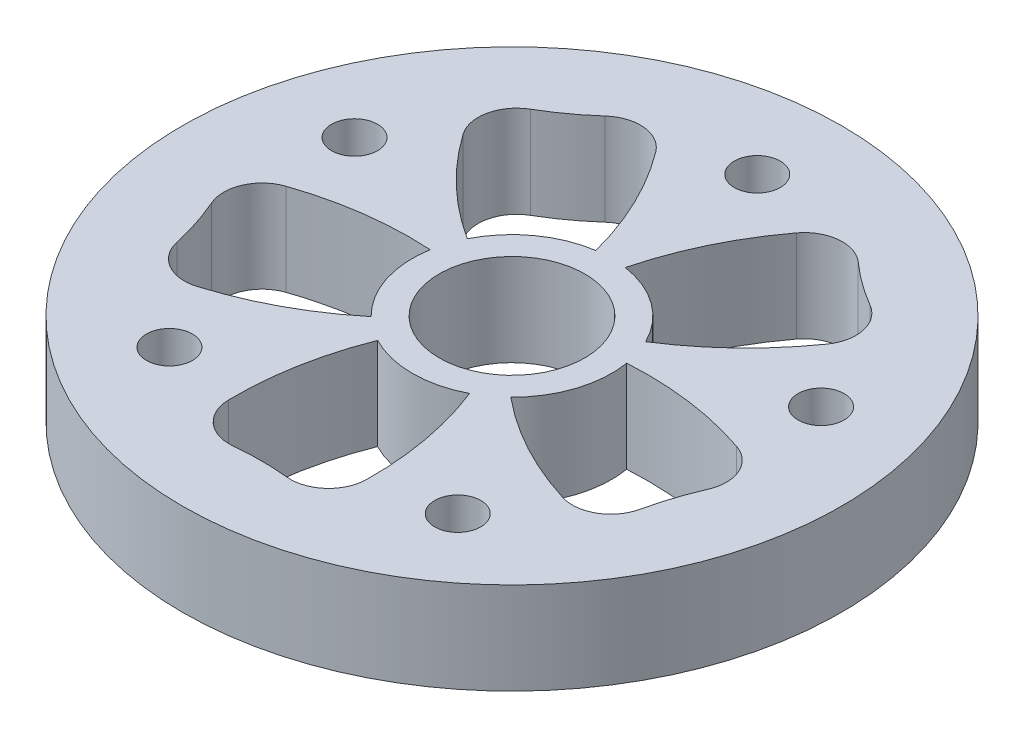
SolidWorks part; units mm, degrees
ref_plane "前视基准面" through (0, 0, 0) normal (0, 0, 1) x (1, 0, 0)
ref_plane "上视基准面" through (0, 0, 0) normal (0, 1, 0) x (1, 0, 0)
ref_plane "右视基准面" through (0, 0, 0) normal (1, 0, 0) x (0, 0, -1)
other "Configuration Table"
sketch "草图1" plane through (0, 0, 0) normal (0, 1, 0) x (1, 0, 0)
  line L0 (0, -43) -> (0, 43) construction
  line L1 (0, 0) -> (0, 32) construction
  circle A0 centre (0, 0) radius 32 construction
  circle A1 centre (0, 0) radius 43
  circle A2 centre (0, 0) radius 9.5
  circle A3 centre (0, 32) radius 3
  circle A4 centre (30.4338, 9.8885) radius 3
  circle A5 centre (18.8091, -25.8885) radius 3
  circle A6 centre (-18.8091, -25.8885) radius 3
  circle A7 centre (-30.4338, 9.8885) radius 3
  point P10 (0, 0)
  dimension "D1" = 19
  dimension "D2" = 64
  dimension "D3" = 86
  dimension "D4" = 6
  dimension "D6" = 32
  dimension "D5" = 5
extrude "凸台-拉伸1" add sketch "草图1" along normal blind 12
sketch "草图2" plane through (0, 0, 0) normal (0, 1, 0) x (1, 0, 0)
  line L0 (0, 0) -> (0, -106.706) construction
  line L1 (0, 0) -> (6, -11.5326) construction
  circle A0 centre (0, 0) radius 13
  arc A1 (-6, -11.5326) -> (-8.9994, -28) centre (33.9953, -27.3242) ccw
  arc A2 (-8.9994, -28) -> (-3.5, -32.8964) centre (-4, -27.9214) ccw
  arc A3 (6, -11.5326) -> (8.9994, -28) centre (-33.9953, -27.3242) cw
  arc A4 (8.9994, -28) -> (3.5, -32.8964) centre (4, -27.9214) cw
  arc A5 (-3.5, -32.8964) -> (3.5, -32.8964) centre (0, -67.7209) cw
  arc A6 (-29.4105, -0.0936) -> (-32.3679, -6.8368) centre (-27.7909, -4.824) ccw
  arc A7 (-12.8222, 2.1426) -> (-29.4105, -0.0936) centre (-15.4817, -40.7751) ccw
  arc A8 (-32.3679, -6.8368) -> (-30.2047, -13.4942) centre (-64.4064, -20.9269) cw
  arc A9 (-23.8486, -17.2114) -> (-30.2047, -13.4942) centre (-25.3188, -12.4324) cw
  arc A10 (-9.114, -9.2701) -> (-23.8486, -17.2114) centre (-36.492, 23.8878) cw
  arc A11 (-9.1773, 27.9422) -> (-16.5044, 28.671) centre (-13.1757, 24.94) ccw
  arc A12 (-1.9246, 12.8568) -> (-9.1773, 27.9422) centre (-43.5635, 2.1238) ccw
  arc A13 (-16.5044, 28.671) -> (-22.1676, 24.5565) centre (-39.8054, 54.7874) cw
  arc A14 (-23.7386, 17.3628) -> (-22.1676, 24.5565) centre (-19.6479, 20.2378) cw
  arc A15 (-11.6328, 5.8033) -> (-23.7386, 17.3628) centre (11.442, 42.0877) cw
  arc A16 (23.7386, 17.3628) -> (22.1676, 24.5565) centre (19.6479, 20.2378) ccw
  arc A17 (11.6328, 5.8033) -> (23.7386, 17.3628) centre (-11.442, 42.0877) ccw
  arc A18 (22.1676, 24.5565) -> (16.5044, 28.671) centre (39.8054, 54.7874) cw
  arc A19 (9.1773, 27.9422) -> (16.5044, 28.671) centre (13.1757, 24.94) cw
  arc A20 (1.9246, 12.8568) -> (9.1773, 27.9422) centre (43.5635, 2.1238) cw
  arc A21 (23.8486, -17.2114) -> (30.2047, -13.4942) centre (25.3188, -12.4324) ccw
  arc A22 (9.114, -9.2701) -> (23.8486, -17.2114) centre (36.492, 23.8878) ccw
  arc A23 (30.2047, -13.4942) -> (32.3679, -6.8368) centre (64.4064, -20.9269) cw
  arc A24 (29.4105, -0.0936) -> (32.3679, -6.8368) centre (27.7909, -4.824) cw
  arc A25 (12.8222, 2.1426) -> (29.4105, -0.0936) centre (15.4817, -40.7751) cw
  point P9 (0, 0)
  dimension "D1" = 26
  dimension "D2" = 43
  dimension "D3" = 5
  dimension "D4" = 28
  dimension "D5" = 7
  dimension "D6" = 8
  dimension "D7" = 6
  dimension "D9" = 13
  dimension "D8" = 5
extrude "切除-拉伸1" cut sketch "草图2" along normal through all both and the other way through all contours A10 A0 A7 A6 A8 A9 | A2 A5 A4 A3 A0 A1 | A25 A0 A22 A21 A23 A24 | A20 A0 A17 A16 A18 A19 | A15 A0 A12 A11 A13 A14
